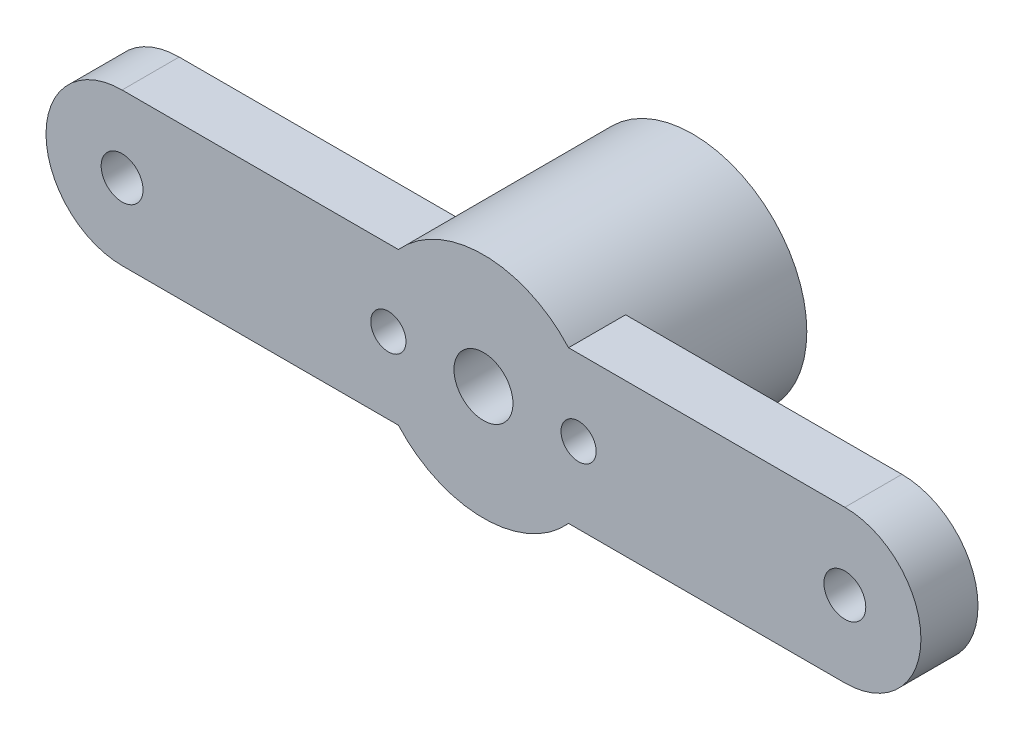
SolidWorks part; units mm, degrees
ref_plane "前视基准面" through (0, 0, 0) normal (0, 0, 1) x (1, 0, 0)
ref_plane "上视基准面" through (0, 0, 0) normal (0, 1, 0) x (1, 0, 0)
ref_plane "右视基准面" through (0, 0, 0) normal (1, 0, 0) x (0, 0, -1)
sketch "草图1" plane through (0, 0, 0) normal (0, 0, 1) x (1, 0, 0)
  line L0 (4.4721, 4) -> (19, 4)
  line L1 (-19, -4) -> (-4.4721, -4)
  line L2 (4.4721, -4) -> (19, -4)
  line L3 (-19, 4) -> (-4.4721, 4)
  circle A0 centre (0, 0) radius 1.55
  circle A1 centre (19, 0) radius 1.1
  circle A2 centre (-19, 0) radius 1.1
  arc A3 (-19, 4) -> (-19, -4) centre (-19, 0) ccw
  arc A4 (19, -4) -> (19, 4) centre (19, 0) ccw
  arc A5 (-4.4721, -4) -> (4.4721, -4) centre (0, 0) ccw
  arc A6 (4.4721, 4) -> (-4.4721, 4) centre (0, 0) ccw
  circle A7 centre (-5, 0) radius 0.925
  circle A8 centre (5, 0) radius 0.925
  dimension "D3" = 2.2
  dimension "D4" = 2.2
  dimension "D5" = 3.1
  dimension "D8" = 12
  dimension "D7" = 8
  dimension "D9" = 4
  dimension "D6" = 8
  dimension "D11" = 1.85
  dimension "D12" = 1.85
  dimension "D1" = 19
  dimension "D2" = 19
  dimension "D10" = 4
  dimension "D13" = 5
  dimension "D14" = 5
extrude "凸台-拉伸1" add sketch "草图1" along normal blind 3
sketch "草图2" plane through (0, 0, 0) normal (0, 0, -1) x (-1, 0, 0)
  circle A0 centre (0, 0) radius 6
  circle A1 centre (0, 0) radius 1.55
  circle A2 centre (-5, 0) radius 0.925
  circle A3 centre (5, 0) radius 0.925
  dimension "D1" = 3.1
extrude "凸台-拉伸2" add sketch "草图2" along normal blind 8
